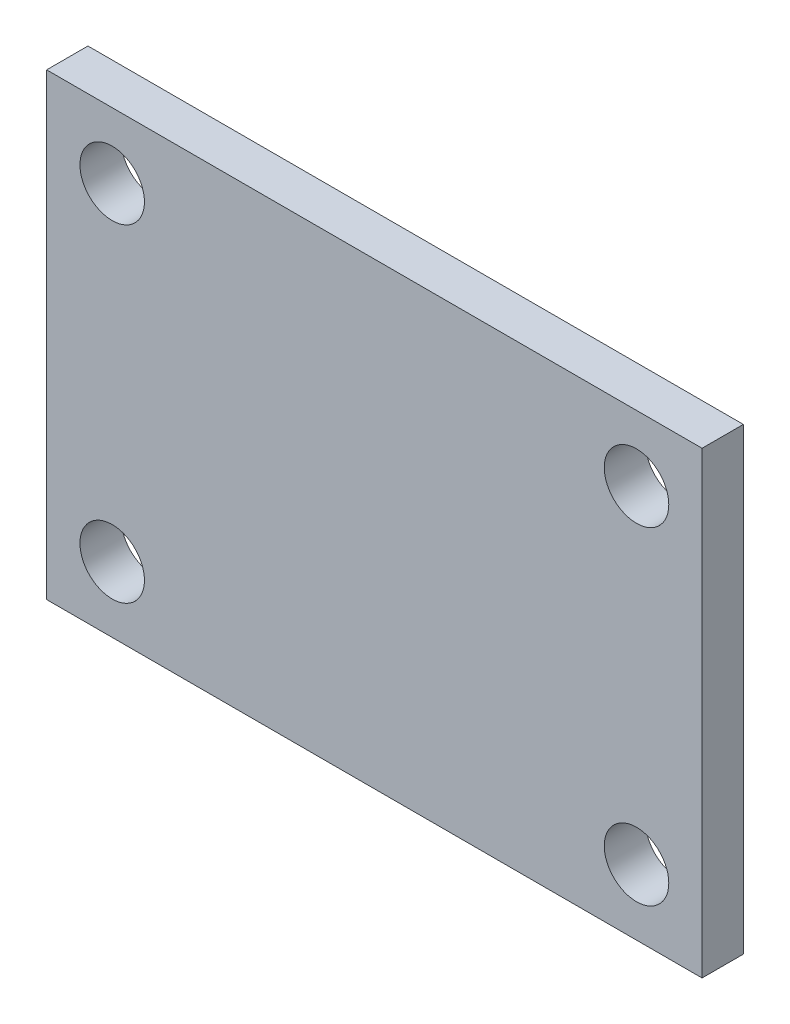
SolidWorks part; units mm, degrees
ref_plane "Front Plane" through (0, 0, 0) normal (0, 0, 1) x (1, 0, 0)
ref_plane "Top Plane" through (0, 0, 0) normal (0, 1, 0) x (1, 0, 0)
ref_plane "Right Plane" through (0, 0, 0) normal (1, 0, 0) x (0, 0, -1)
sketch "PCB_25p4x17p78x1p6_M2p5_Profile" plane through (0, 0, 0) normal (0, 0, 1) x (1, 0, 0)
  line L1 (-0.2, -8.89) -> (25.2, -8.89)
  line L2 (-0.2, -8.89) -> (-0.2, 8.89)
  line L3 (-0.2, 8.89) -> (25.2, 8.89)
  line L4 (25.2, -8.89) -> (25.2, 8.89)
  circle A0 centre (2.34, 6.35) radius 1.25
  circle A1 centre (22.66, 6.35) radius 1.25
  circle A2 centre (2.34, -6.35) radius 1.25
  circle A3 centre (22.66, -6.35) radius 1.25
extrude "PCB_25p4x17p78x1p6_M2p5" add sketch "PCB_25p4x17p78x1p6_M2p5_Profile" along normal blind 1.6 from offset 24.15
